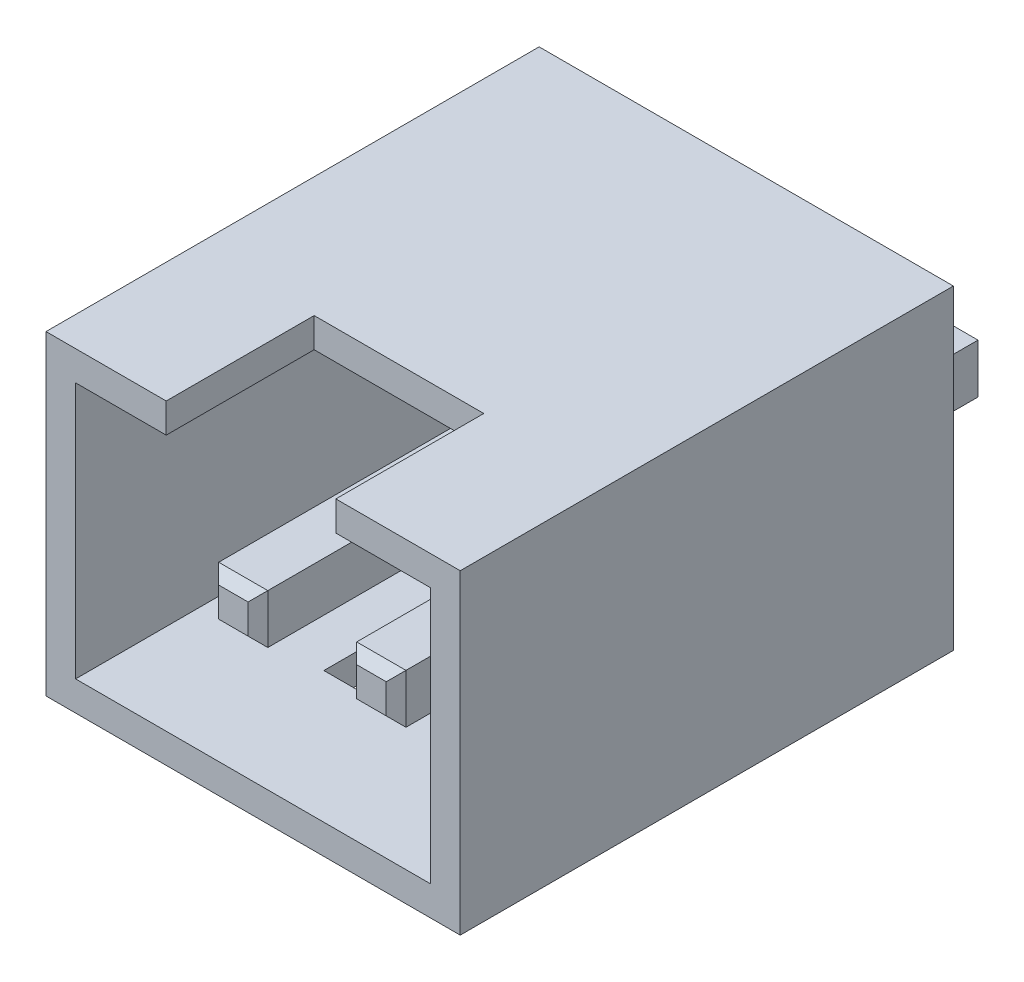
SolidWorks part; units mm, degrees
ref_plane "前视基准面" through (0, 0, 0) normal (0, 0, 1) x (1, 0, 0)
ref_plane "上视基准面" through (0, 0, 0) normal (0, 1, 0) x (1, 0, 0)
ref_plane "右视基准面" through (0, 0, 0) normal (1, 0, 0) x (0, 0, -1)
sketch "草图1" plane through (0, 0, 0) normal (0, 0, 1) x (1, 0, 0)
  line L1 (-2.1, 1.6) -> (2.1, 1.6)
  line L2 (-2.1, 1.6) -> (-2.1, -1.6)
  line L3 (-2.1, -1.6) -> (2.1, -1.6)
  line L4 (2.1, 1.6) -> (2.1, -1.6)
  line L5 (-2.1, 1.6) -> (2.1, -1.6) construction
  line L6 (-2.1, -1.6) -> (2.1, 1.6) construction
  point P0 (0, 0)
extrude "凸台-拉伸1" add sketch "草图1" along normal blind 5
sketch "草图2" plane through (0, 0, 5) normal (0, 0, 1) x (1, 0, 0)
  line L1 (-1.8, 1.3) -> (1.8, 1.3)
  line L2 (-1.8, 1.3) -> (-1.8, -1.3)
  line L3 (-1.8, -1.3) -> (1.8, -1.3)
  line L4 (1.8, 1.3) -> (1.8, -1.3)
  line L5 (-1.8, 1.3) -> (1.8, -1.3) construction
  line L6 (-1.8, -1.3) -> (1.8, 1.3) construction
  point P0 (0, 0)
extrude "切除-拉伸2" cut sketch "草图2" against normal blind 4.5
sketch "草图10" plane through (0, 0, 5) normal (0, 0, 1) x (1, 0, 0)
  line L0 (2.1, 1.6) -> (-2.1, 1.6) construction
  line L1 (-0.8811, 1.6) -> (0.8388, 1.6)
  line L2 (-0.8811, 1.6) -> (-0.8811, 1.3)
  line L3 (-0.8811, 1.3) -> (0.8388, 1.3)
  line L4 (0.8388, 1.6) -> (0.8388, 1.3)
  line L5 (1.8, 1.3) -> (-1.8, 1.3) construction
extrude "切除-拉伸6" cut sketch "草图10" against normal blind 1.5
sketch "草图12" plane through (0, 0, 0.5) normal (0, 0, 1) x (1, 0, 0)
  line L5 (-0.949, -0.15) -> (-0.451, -0.15)
  line L6 (-0.949, -0.15) -> (-0.949, -0.65)
  line L7 (-0.949, -0.65) -> (-0.451, -0.65)
  line L8 (-0.451, -0.15) -> (-0.451, -0.65)
  line L9 (-0.949, -0.15) -> (-0.451, -0.65) construction
  line L10 (-0.949, -0.65) -> (-0.451, -0.15) construction
  line L11 (0.4502, -0.15) -> (0.9498, -0.15)
  line L12 (0.4502, -0.15) -> (0.4502, -0.65)
  line L13 (0.4502, -0.65) -> (0.9498, -0.65)
  line L14 (0.9498, -0.15) -> (0.9498, -0.65)
  line L15 (0.4502, -0.15) -> (0.9498, -0.65) construction
  line L16 (0.4502, -0.65) -> (0.9498, -0.15) construction
extrude "凸台-拉伸2" add sketch "草图12" along normal blind 4 and the other way blind 2
chamfer "倒角2" distance 0.1 angle 45 8 edges at (0.7, -0.65, 4.5) (0.4502, -0.4, 4.5) (0.7, -0.15, 4.5) (0.9498, -0.4, 4.5) (-0.7, -0.65, 4.5) (-0.949, -0.4, 4.5) (-0.7, -0.15, 4.5) (-0.451, -0.4, 4.5)
chamfer "倒角3" distance 0.1 angle 45 8 edges at (0.7, -0.15, -1.5) (0.4502, -0.4, -1.5) (0.7, -0.65, -1.5) (0.9498, -0.4, -1.5) (-0.7, -0.15, -1.5) (-0.949, -0.4, -1.5) (-0.7, -0.65, -1.5) (-0.451, -0.4, -1.5)
sketch "草图13" plane through (0, -1.6, 0) normal (0, -1, 0) x (1, 0, 0)
  line L1 (0.1722, 2.8262) -> (-0.6148, 2.8262)
  line L2 (0.1722, 2.8262) -> (0.1722, 3.6678)
  line L3 (0.1722, 3.6678) -> (-0.6148, 3.6678)
  line L4 (-0.6148, 2.8262) -> (-0.6148, 3.6678)
  line L5 (0.1722, 2.8262) -> (-0.6148, 3.6678) construction
  line L6 (0.1722, 3.6678) -> (-0.6148, 2.8262) construction
  point P0 (-0.2213, 3.247)
extrude "切除-拉伸7" cut sketch "草图13" against normal blind 0.5
